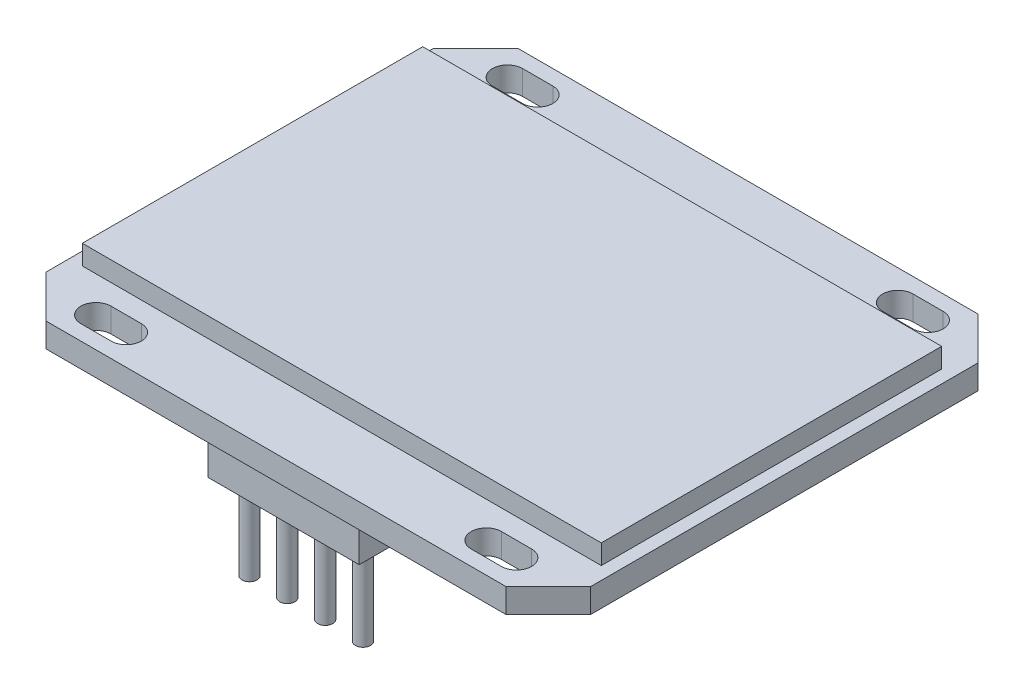
SolidWorks part; units mm, degrees
ref_plane "前视基准面" through (0, 0, 0) normal (0, 0, 1) x (1, 0, 0)
ref_plane "上视基准面" through (0, 0, 0) normal (0, 1, 0) x (1, 0, 0)
ref_plane "右视基准面" through (0, 0, 0) normal (1, 0, 0) x (0, 0, -1)
sketch "草图1" plane through (0, 0, 0) normal (0, 1, 0) x (1, 0, 0)
  line L1 (-18, -15.6) -> (18, -15.6)
  line L2 (-18, -15.6) -> (-18, 15.6)
  line L3 (-18, 15.6) -> (18, 15.6)
  line L4 (18, -15.6) -> (18, 15.6)
  line L5 (-18, -15.6) -> (18, 15.6) construction
  line L6 (-18, 15.6) -> (18, -15.6) construction
  point P0 (0, 0)
  dimension "D1" = 36
  dimension "D2" = 31.2
extrude "凸台-拉伸1" add sketch "草图1" along normal blind 1.6
sketch "草图2" plane through (0, 1.6, 0) normal (0, 1, 0) x (1, 0, 0)
  line L1 (-17.15, -11.25) -> (17.15, -11.25)
  line L2 (-17.15, -11.25) -> (-17.15, 11.25)
  line L3 (-17.15, 11.25) -> (17.15, 11.25)
  line L4 (17.15, -11.25) -> (17.15, 11.25)
  line L5 (-17.15, -11.25) -> (17.15, 11.25) construction
  line L6 (-17.15, 11.25) -> (17.15, -11.25) construction
  point P0 (0, 0)
  dimension "D1" = 34.3
  dimension "D2" = 22.5
extrude "凸台-拉伸2" add sketch "草图2" along normal blind 1.3
sketch "草图3" plane through (0, 1.6, 0) normal (0, 1, 0) x (1, 0, 0)
  line L0 (18, 15.6) -> (-18, 15.6) construction
  line L1 (0, 15.6) -> (0, -15.6) construction
  line L2 (-18, -15.6) -> (18, -15.6) construction
  line L3 (-18, 0) -> (18, 0) construction
  line L4 (-18, 15.6) -> (-18, -15.6) construction
  line L5 (18, -15.6) -> (18, 15.6) construction
  line L6 (-13.9, 13.6) -> (-11.9, 13.6) construction
  line L7 (-13.9, 14.6) -> (-11.9, 14.6)
  line L8 (-13.9, 12.6) -> (-11.9, 12.6)
  line L9 (13.9, 13.6) -> (11.9, 13.6) construction
  line L10 (13.9, 14.6) -> (11.9, 14.6)
  line L11 (13.9, 12.6) -> (11.9, 12.6)
  line L12 (13.9, -13.6) -> (11.9, -13.6) construction
  line L13 (13.9, -14.6) -> (11.9, -14.6)
  line L14 (13.9, -12.6) -> (11.9, -12.6)
  line L15 (-13.9, -13.6) -> (-11.9, -13.6) construction
  line L16 (-13.9, -14.6) -> (-11.9, -14.6)
  line L17 (-13.9, -12.6) -> (-11.9, -12.6)
  arc A0 (-13.9, 14.6) -> (-13.9, 12.6) centre (-13.9, 13.6) ccw
  arc A1 (-11.9, 12.6) -> (-11.9, 14.6) centre (-11.9, 13.6) ccw
  arc A2 (13.9, 14.6) -> (13.9, 12.6) centre (13.9, 13.6) cw
  arc A3 (11.9, 12.6) -> (11.9, 14.6) centre (11.9, 13.6) cw
  arc A4 (13.9, -14.6) -> (13.9, -12.6) centre (13.9, -13.6) ccw
  arc A5 (11.9, -12.6) -> (11.9, -14.6) centre (11.9, -13.6) ccw
  arc A6 (-13.9, -14.6) -> (-13.9, -12.6) centre (-13.9, -13.6) cw
  arc A7 (-11.9, -12.6) -> (-11.9, -14.6) centre (-11.9, -13.6) cw
  point P14 (-12.9, 13.6)
  point P19 (-12.7037, 13.2533)
  point P22 (12.9, 13.6)
  point P29 (12.9, -13.6)
  point P36 (-12.9, -13.6)
  dimension "D2" = 2
  dimension "D1" = 2
  dimension "D3" = 1
  dimension "D4" = 25.8
extrude "切除-拉伸1" cut sketch "草图3" against normal through all
chamfer "倒角1" distance 2.8 angle 45 3 edges at (18, 0.8, 15.6) (18, 0.8, -15.6) (-18, 0.8, -15.6)
sketch "草图4" plane through (0, 0, 0) normal (0, -1, 0) x (1, 0, 0)
  line L0 (0, 15.6) -> (0, -15.6) construction
  line L1 (-15.2, 15.6) -> (15.2, 15.6) construction
  line L2 (15.2, -15.6) -> (-15.2, -15.6) construction
  line L4 (-5, 12.6) -> (5, 12.6)
  line L5 (-5, 12.6) -> (-5, 15.1)
  line L6 (-5, 15.1) -> (5, 15.1)
  line L7 (5, 12.6) -> (5, 15.1)
  line L8 (-5, 12.6) -> (5, 15.1) construction
  line L9 (-5, 15.1) -> (5, 12.6) construction
  point P6 (0, 13.85)
  point P11 (0, 14.7876)
  dimension "D1" = 0.5
  dimension "D2" = 10
  dimension "D3" = 2.5
extrude "凸台-拉伸3" add sketch "草图4" along normal blind 2.5
sketch "草图5" plane through (0, -2.5, 0) normal (0, -1, 0) x (1, 0, 0)
  line L2 (-5, 13.85) -> (0.1466, 13.85) construction
  line L3 (-5, 15.1) -> (-5, 12.6) construction
  circle A0 centre (-3.5, 13.85) radius 0.5
  point P2 (-3.7977, 13.85)
  point P3 (0, 0)
  point P4 (0, 0)
  dimension "D1" = 1
  dimension "D2" = 1.5
extrude "凸台-拉伸4" add sketch "草图5" along normal blind 5.5
pattern_linear "阵列(线性)1" count 4 spacing 2.5 along (1, 0, 0) of "凸台-拉伸4"
